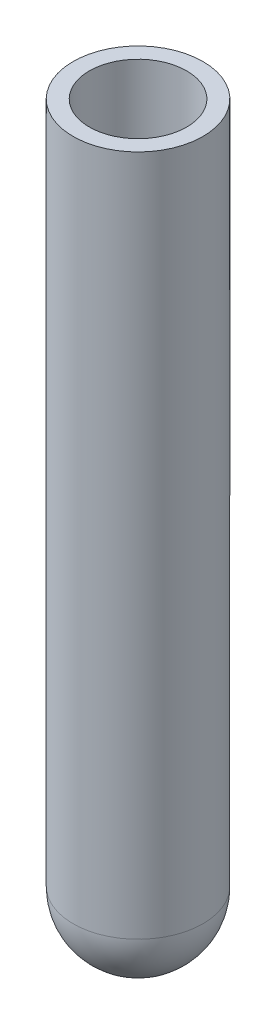
SolidWorks part; units mm, degrees
ref_plane "Alzado" through (0, 0, 0) normal (0, 0, 1) x (1, 0, 0)
ref_plane "Planta" through (0, 0, 0) normal (0, 1, 0) x (1, 0, 0)
ref_plane "Vista lateral" through (0, 0, 0) normal (1, 0, 0) x (0, 0, -1)
sketch "Croquis1" plane through (0, 0, 0) normal (0, 0, 1) x (1, 0, 0)
  line L0 (0, 0) -> (8, 0) construction
  line L1 (0, 0) -> (0, 58) construction
  line L2 (0, 0) -> (0, -34) construction
  line L3 (8, -34) -> (8, 50)
  line L4 (8, 50) -> (6, 50)
  line L5 (6, 50) -> (6, -34)
  line L6 (0, -40) -> (0, -42)
  arc A0 (0, -42) -> (8, -34) centre (0, -34) ccw
  arc A1 (0, -40) -> (6, -34) centre (0, -34) ccw
  dimension "D1" = 100
  dimension "D4" = 2
  dimension "D2" = 8
  dimension "D3" = 2
revolve "Revolución1" add sketch "Croquis1" angle 360 about L1
